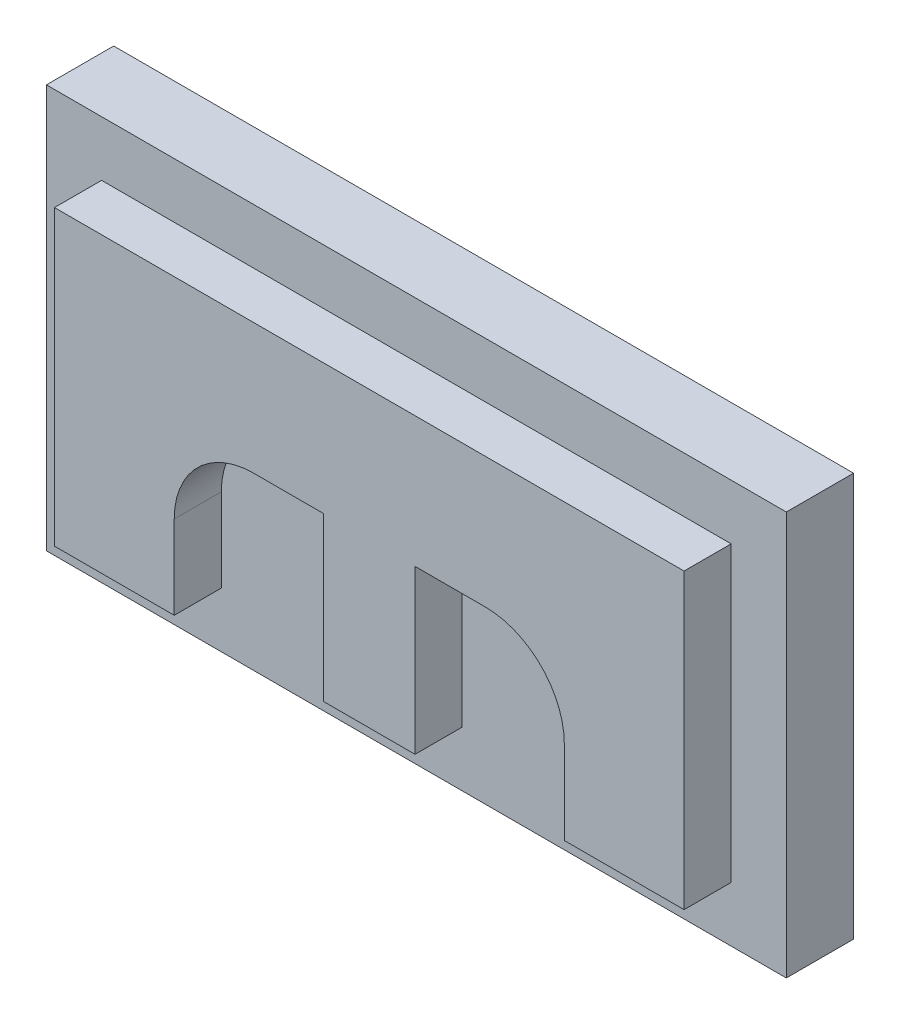
SolidWorks part; units mm, degrees
ref_plane "Front Plane" through (0, 0, 0) normal (0, 0, 1) x (1, 0, 0)
ref_plane "Top Plane" through (0, 0, 0) normal (0, 1, 0) x (1, 0, 0)
ref_plane "Right Plane" through (0, 0, 0) normal (1, 0, 0) x (0, 0, -1)
sketch "Sketch1" plane through (0, 0, 0) normal (0, 0, 1) x (1, 0, 0)
  line L1 (0, 0) -> (110, 0)
  line L2 (0, 0) -> (0, 60)
  line L3 (0, 60) -> (110, 60)
  line L4 (110, 0) -> (110, 60)
  dimension "D1" = 110
  dimension "D2" = 60
extrude "Boss-Extrude1" add sketch "Sketch1" along normal blind 10
sketch "Sketch3" plane through (0, 0, 10) normal (0, 0, 1) x (1, 0, 0)
  line L0 (110, 60) -> (0, 60) construction
  line L1 (8.2, 51.8) -> (101.8, 51.8)
  line L2 (8.2, 51.8) -> (8.2, 8.2)
  line L3 (8.2, 8.2) -> (101.8, 8.2)
  line L4 (101.8, 51.8) -> (101.8, 8.2)
  line L5 (0, 60) -> (0, 0) construction
  line L6 (0, 0) -> (110, 0) construction
  line L7 (110, 0) -> (110, 60) construction
  dimension "D1" = 93.6
  dimension "D2" = 43.6
  dimension "D3" = 8.2
  dimension "D4" = 8.2
  dimension "D5" = 8.2
  dimension "D6" = 8.2
extrude "Boss-Extrude2" add sketch "Sketch3" along normal blind 7
sketch "Sketch4" plane through (0, 0, 17) normal (0, 0, 1) x (1, 0, 0)
  line L0 (8.2, 51.8) -> (8.2, 8.2) construction
  line L1 (26, 32.4) -> (48.2, 32.4)
  line L2 (26, 32.4) -> (26, 8.2)
  line L3 (26, 8.2) -> (48.2, 8.2)
  line L4 (48.2, 32.4) -> (48.2, 8.2)
  line L5 (8.2, 8.2) -> (101.8, 8.2) construction
  dimension "D1" = 17.8
  dimension "D2" = 22.2
  dimension "D3" = 24.2
  dimension "D4" = 0
extrude "Cut-Extrude1" cut sketch "Sketch4" against normal blind 7
fillet "Fillet1" radius 11.8 1 edges at (26, 32.4, 13.5)
sketch "Sketch5" plane through (0, 0, 0) normal (0, 0, 1) x (1, 0, 0)
  line L0 (55, 60) -> (55, 0) construction
  line L1 (110, 60) -> (0, 60) construction
  line L2 (0, 0) -> (110, 0) construction
ref_plane "Plane1" through (55, 0, 0) normal (-1, 0, 0) x (0, -1, 0)
mirror "Mirror1" about plane through (55, 0, 0) normal (-1, 0, 0) of "Fillet1", "Cut-Extrude1"
